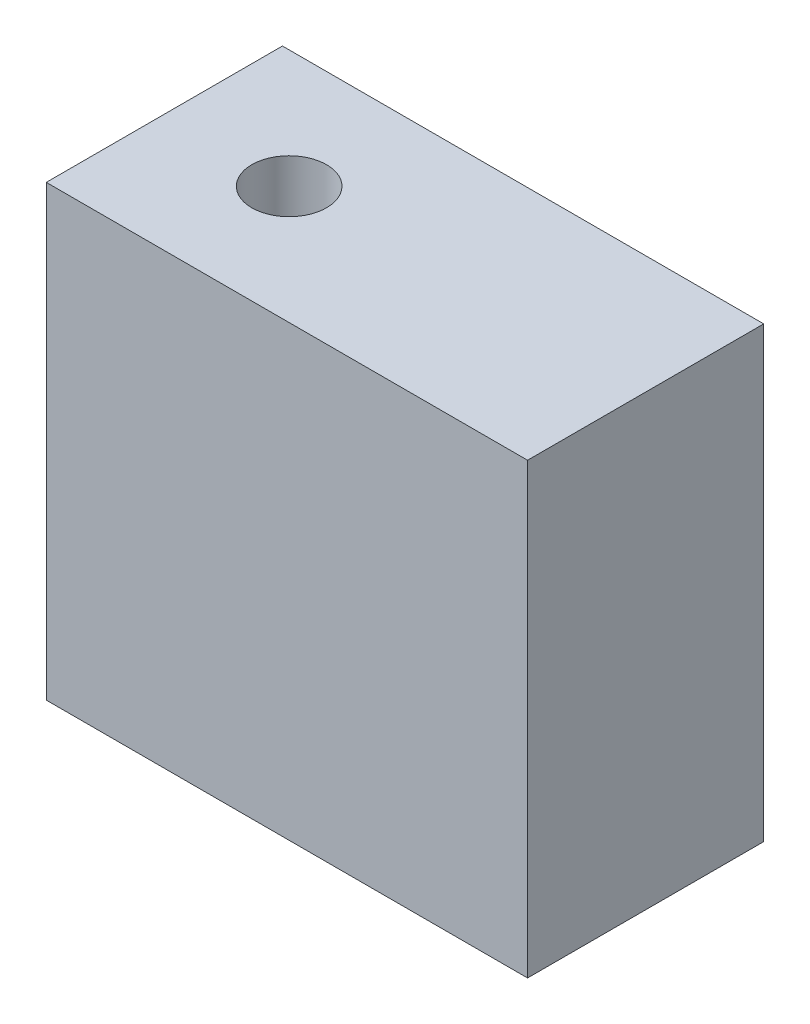
SolidWorks part; units mm, degrees
material "6061-T6 (SS)"
ref_plane "Front Plane" through (0, 0, 0) normal (0, 0, 1) x (1, 0, 0)
ref_plane "Top Plane" through (0, 0, 0) normal (0, 1, 0) x (1, 0, 0)
ref_plane "Right Plane" through (0, 0, 0) normal (1, 0, 0) x (0, 0, -1)
sketch "Sketch1" plane through (0, 0, 0) normal (0, 1, 0) x (1, 0, 0)
  line L1 (0, 0) -> (-40.894, 0)
  line L2 (0, 0) -> (0, -20.066)
  line L3 (0, -20.066) -> (-40.894, -20.066)
  line L4 (-40.894, 0) -> (-40.894, -20.066)
  dimension "D1" = 40.894
  dimension "D2" = 20.066
extrude "Boss-Extrude1" add sketch "Sketch1" along normal blind 38.1
sketch "Sketch2" plane through (0, 38.1, 0) normal (0, 1, 0) x (1, 0, 0)
  line L0 (-40.894, -20.066) -> (-30.2895, -20.066) construction
  line L1 (-40.894, -20.066) -> (0, -20.066) construction
  line L2 (-30.2895, -20.066) -> (-30.2895, 0) construction
  line L3 (0, 0) -> (-40.894, 0) construction
  circle A0 centre (-30.2895, -10.033) radius 3.175
  dimension "D1" = 6.35
extrude "Cut-Extrude1" cut sketch "Sketch2" against normal blind 12.7
